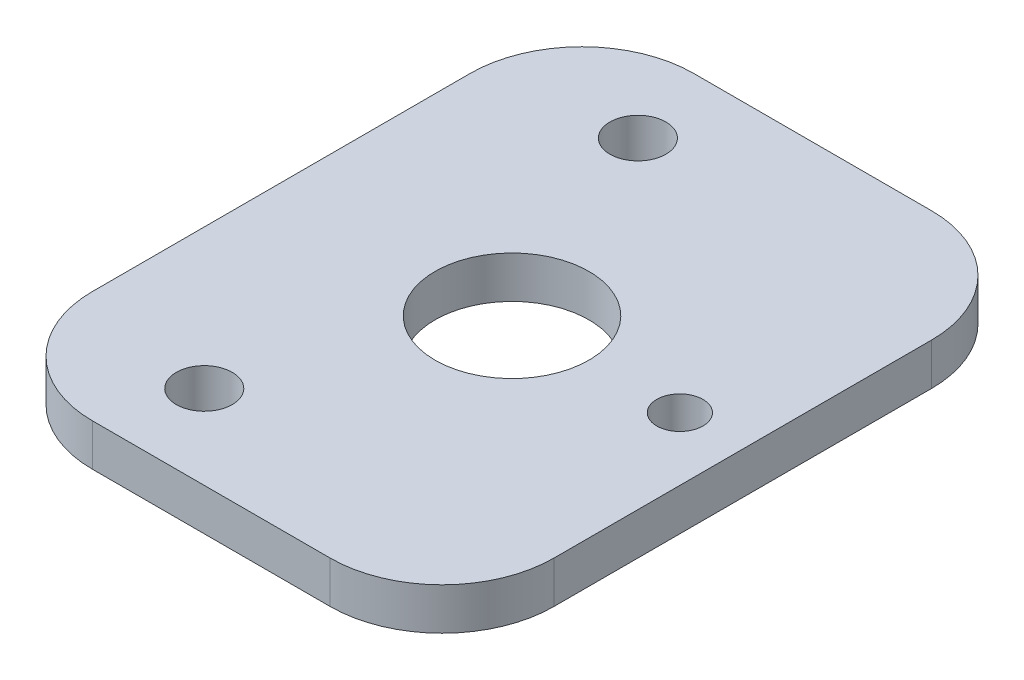
SolidWorks part; units mm, degrees
ref_plane "Front Plane" through (0, 0, 0) normal (0, 0, 1) x (1, 0, 0)
ref_plane "Top Plane" through (0, 0, 0) normal (0, 1, 0) x (1, 0, 0)
ref_plane "Right Plane" through (0, 0, 0) normal (1, 0, 0) x (0, 0, -1)
sketch "Sketch1" plane through (0, 0, 0) normal (0, 1, 0) x (1, 0, 0)
  line L1 (-16.5, 21.5) -> (16.5, 21.5)
  line L2 (-16.5, 21.5) -> (-16.5, -21.5)
  line L3 (-16.5, -21.5) -> (16.5, -21.5)
  line L4 (16.5, 21.5) -> (16.5, -21.5)
  line L5 (-16.5, 21.5) -> (16.5, -21.5) construction
  line L6 (-16.5, -21.5) -> (16.5, 21.5) construction
  circle A0 centre (0, 0) radius 5.5
  point P0 (0, 0)
  dimension "D3" = 11
  dimension "D1" = 43
  dimension "D2" = 33
extrude "Boss-Extrude1" add sketch "Sketch1" along normal blind 3
sketch "Sketch2" plane through (0, 3, 0) normal (0, 1, 0) x (1, 0, 0)
  circle A0 centre (-6.5, 15.5) radius 2
  circle A1 centre (-6.5, -15.5) radius 2
  circle A2 centre (12, 0) radius 1.65
  dimension "D1" = 3.3
  dimension "D2" = 12
extrude "Cut-Extrude1" cut sketch "Sketch2" against normal blind 10
fillet "Fillet1" radius 8 4 edges at (16.5, 1.5, -21.5) (16.5, 1.5, 21.5) (-16.5, 1.5, 21.5) (-16.5, 1.5, -21.5)
